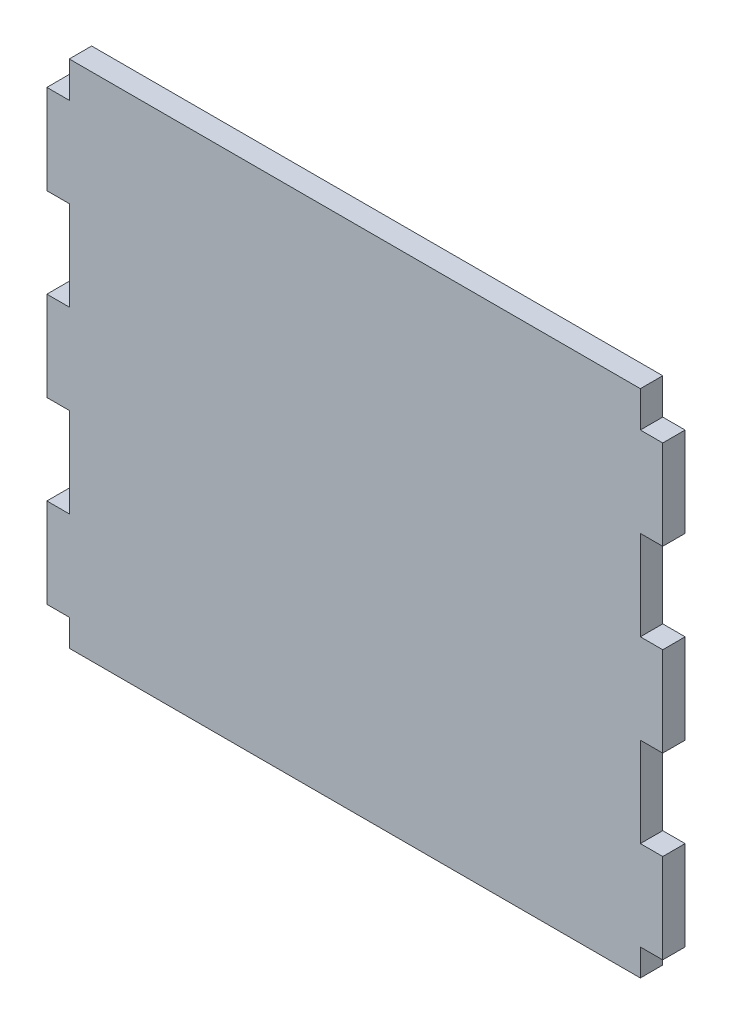
SolidWorks part; units mm, degrees
material "Acrylic (Medium-high impact)"
ref_plane "Front Plane" through (0, 0, 0) normal (0, 0, 1) x (1, 0, 0)
ref_plane "Top Plane" through (0, 0, 0) normal (0, 1, 0) x (1, 0, 0)
ref_plane "Right Plane" through (0, 0, 0) normal (1, 0, 0) x (0, 0, -1)
sketch "Sketch1" plane through (0, 0, 0) normal (0, 0, 1) x (1, 0, 0)
  line L0 (0, 0) -> (0, 5.08) construction
  line L1 (0, 5.08) -> (-3.175, 5.08)
  line L2 (-3.175, 5.08) -> (-3.175, 17.78)
  line L3 (-3.175, 17.78) -> (0, 17.78)
  line L4 (0, 17.78) -> (0, 30.48)
  line L5 (0, 30.48) -> (-3.175, 30.48)
  line L6 (-3.175, 30.48) -> (-3.175, 43.18)
  line L7 (-3.175, 43.18) -> (0, 43.18)
  line L8 (0, 43.18) -> (0, 55.88)
  line L9 (0, 55.88) -> (-3.175, 55.88)
  line L10 (-3.175, 55.88) -> (-3.175, 68.58)
  line L11 (-3.175, 68.58) -> (0, 68.58)
  line L12 (0, 68.58) -> (0, 73.66)
  line L13 (0, 73.66) -> (81, 73.66)
  line L14 (40.5, 73.66) -> (40.5, 0) construction
  line L15 (81, 0) -> (0, 0) construction
  line L16 (81, 68.58) -> (81, 73.66)
  line L17 (84.175, 68.58) -> (81, 68.58)
  line L18 (84.175, 55.88) -> (84.175, 68.58)
  line L19 (81, 55.88) -> (84.175, 55.88)
  line L20 (81, 43.18) -> (81, 55.88)
  line L21 (84.175, 43.18) -> (81, 43.18)
  line L22 (84.175, 30.48) -> (84.175, 43.18)
  line L23 (81, 30.48) -> (84.175, 30.48)
  line L24 (81, 17.78) -> (81, 30.48)
  line L25 (84.175, 17.78) -> (81, 17.78)
  line L26 (84.175, 5.08) -> (84.175, 17.78)
  line L27 (81, 5.08) -> (84.175, 5.08)
  line L28 (81, 0) -> (81, 5.08) construction
  line L29 (0, 1.27) -> (81, 1.27)
  line L30 (0, 5.08) -> (0, 1.27)
  line L31 (81, 5.08) -> (81, 1.27)
  dimension "D1" = 12.7
  dimension "D2" = 73.66
  dimension "D3" = 40.5
  dimension "D4" = 3.175
  dimension "D5" = 3.81
extrude "Boss-Extrude1" add sketch "Sketch1" along normal blind 3.175
